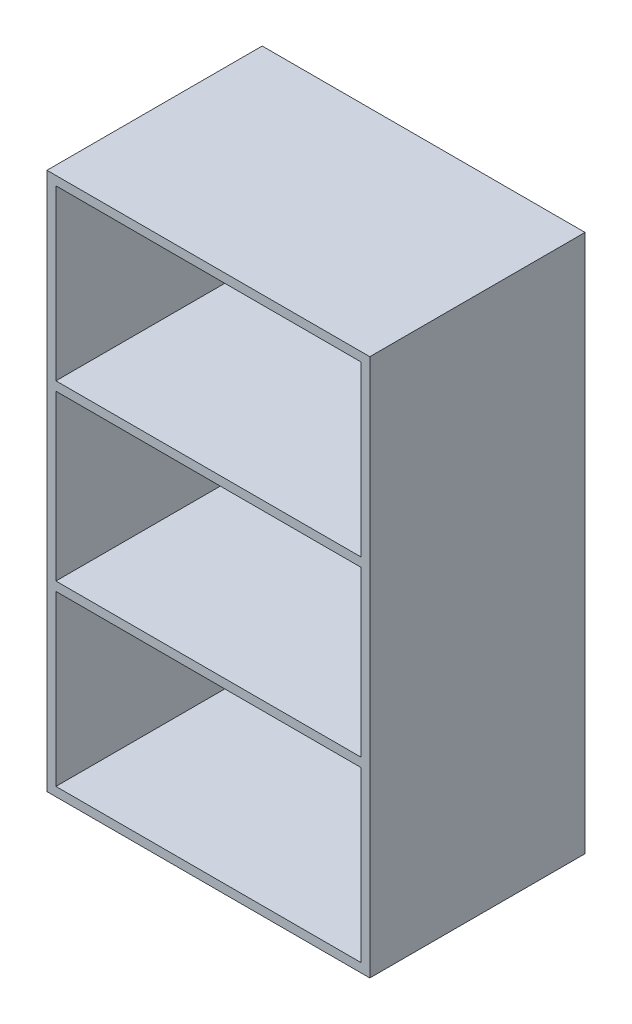
SolidWorks part; units mm, degrees
ref_plane "Front" through (0, 0, 0) normal (0, 0, 1) x (1, 0, 0)
ref_plane "Top" through (0, 0, 0) normal (0, 1, 0) x (1, 0, 0)
ref_plane "Right" through (0, 0, 0) normal (1, 0, 0) x (0, 0, -1)
sketch "Sketch1" plane through (0, 0, 0) normal (0, 1, 0) x (1, 0, 0)
  line L1 (-457.2, 304.8) -> (457.2, 304.8)
  line L2 (-457.2, 304.8) -> (-457.2, -304.8)
  line L3 (-457.2, -304.8) -> (457.2, -304.8)
  line L4 (457.2, 304.8) -> (457.2, -304.8)
  line L5 (-457.2, 304.8) -> (457.2, -304.8) construction
  line L6 (-457.2, -304.8) -> (457.2, 304.8) construction
  point P0 (0, 0)
  dimension "D1" = 914.4
  dimension "D2" = 609.6
extrude "Boss-Extrude1" add sketch "Sketch1" along normal blind 1524
sketch "Sketch2" plane through (0, 0, 304.8) normal (0, 0, 1) x (1, 0, 0)
  line L0 (-431.8, 25.4) -> (431.8, 25.4)
  line L1 (431.8, 25.4) -> (431.8, 503.7667)
  line L2 (431.8, 1498.6) -> (-431.8, 1498.6)
  line L3 (-431.8, 1498.6) -> (-431.8, 1020.2333)
  line L4 (-457.2, 0) -> (457.2, 0)
  line L5 (457.2, 0) -> (457.2, 1524)
  line L6 (457.2, 1524) -> (-457.2, 1524)
  line L7 (-457.2, 1524) -> (-457.2, 0)
  line L8 (-457.2, 0) -> (457.2, 0) construction
  line L9 (457.2, 0) -> (457.2, 1524) construction
  line L10 (457.2, 1524) -> (-457.2, 1524) construction
  line L11 (-457.2, 1524) -> (-457.2, 0) construction
  line L12 (-431.8, 1007.5333) -> (431.8, 1007.5333) construction
  line L13 (-431.8, 516.4667) -> (431.8, 516.4667) construction
  line L14 (0, 1007.5333) -> (0, 1498.6) construction
  line L15 (0, 1007.5333) -> (0, 516.4667) construction
  line L16 (0, 516.4667) -> (0, 25.4) construction
  line L17 (-431.8, 994.8333) -> (431.8, 994.8333)
  line L18 (-431.8, 503.7667) -> (431.8, 503.7667)
  line L19 (-431.8, 1020.2333) -> (431.8, 1020.2333)
  line L20 (-431.8, 529.1667) -> (431.8, 529.1667)
  line L21 (-431.8, 994.8333) -> (-431.8, 529.1667)
  line L22 (-431.8, 1498.6) -> (-431.8, 25.4) construction
  line L23 (-431.8, 503.7667) -> (-431.8, 25.4)
  line L24 (431.8, 529.1667) -> (431.8, 994.8333)
  line L25 (431.8, 25.4) -> (431.8, 1498.6) construction
  line L26 (431.8, 1020.2333) -> (431.8, 1498.6)
  dimension "D1" = 0
  dimension "D2" = 25.4
  dimension "D3" = 12.7
  dimension "D4" = 12.7
extrude "Cut-Extrude1" cut sketch "Sketch2" against normal through all
